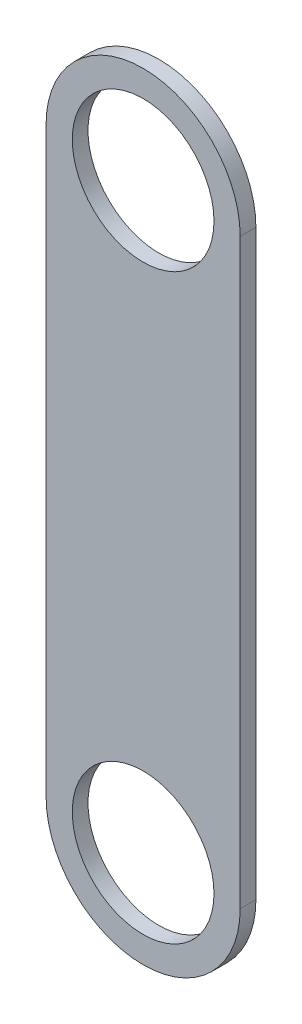
SolidWorks part; units mm, degrees
ref_plane "Front Plane" through (0, 0, 0) normal (0, 0, 1) x (1, 0, 0)
ref_plane "Top Plane" through (0, 0, 0) normal (0, 1, 0) x (1, 0, 0)
ref_plane "Right Plane" through (0, 0, 0) normal (1, 0, 0) x (0, 0, -1)
sketch "Sketch1" plane through (0, 0, 0) normal (0, 0, 1) x (1, 0, 0)
  line L2 (0, 0) -> (0, 76.2)
  line L4 (25.4, 0) -> (25.4, 76.2)
  arc A0 (25.4, 76.2) -> (0, 76.2) centre (12.7, 76.2) ccw
  arc A1 (0, 0) -> (25.4, 0) centre (12.7, 0) ccw
  circle A2 centre (12.7, 76.2) radius 9.271
  circle A3 centre (12.7, 0) radius 9.271
  dimension "D2" = 12.7
  dimension "D3" = 18.542
  dimension "D1" = 76.2
extrude "Boss-Extrude1" add sketch "Sketch1" along normal blind 2.0574
equation "\"Width\"= 0.081"
equation "\"Link Diameter\"= 1"
equation "\"Link Radius\"= \"Link Diameter\" / 2"
equation "\"Length\"= 3"
equation "\"D1@Sketch1\"=\"Length\""
equation "\"D2@Sketch1\"=\"Link Radius\""
equation "\"D1@Boss-Extrude1\"=\"Width\""
equation "\"Bracket Diameter with tol\"= 0.73"
equation "\"D3@Sketch1\"=\"Bracket Diameter with tol\""
